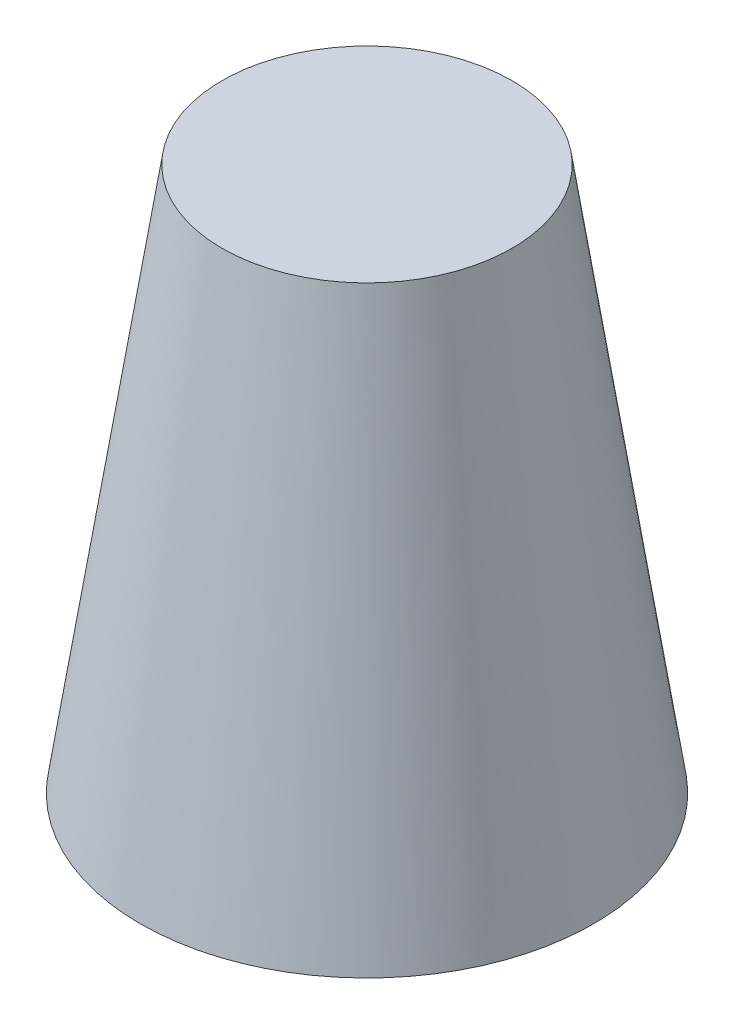
SolidWorks part; units mm, degrees
ref_plane "前视基准面" through (0, 0, 0) normal (0, 0, 1) x (1, 0, 0)
ref_plane "上视基准面" through (0, 0, 0) normal (0, 1, 0) x (1, 0, 0)
ref_plane "右视基准面" through (0, 0, 0) normal (1, 0, 0) x (0, 0, -1)
other "Configuration Table"
sketch "草图2" plane through (0, 0, 0) normal (1, 0, 0) x (0, 0, -1)
  line L0 (0, 0) -> (0, 41.5068) construction
  line L1 (0, 0) -> (51.3276, 0) construction
  line L2 (0, 0) -> (25, 0)
  line L3 (25, 0) -> (16, 60)
  line L4 (16, 60) -> (0, 60)
  line L5 (0, 60) -> (0, 0)
  line L6 (13.4164, 57) -> (3, 57)
  line L7 (3, 57) -> (3, 3)
  line L8 (3, 3) -> (21.5164, 3)
  line L9 (21.5164, 3) -> (13.4164, 57)
  line L10 (3, 57) -> (0, 57)
  line L11 (21.5164, 3) -> (21.9664, 0)
  line L12 (5, 3) -> (5, 0)
  dimension "D1" = 16
  dimension "D2" = 25
  dimension "D3" = 60
  dimension "D4" = 3
  dimension "D5" = 5
revolve "旋转2" add sketch "草图2" angle 360 about L5
